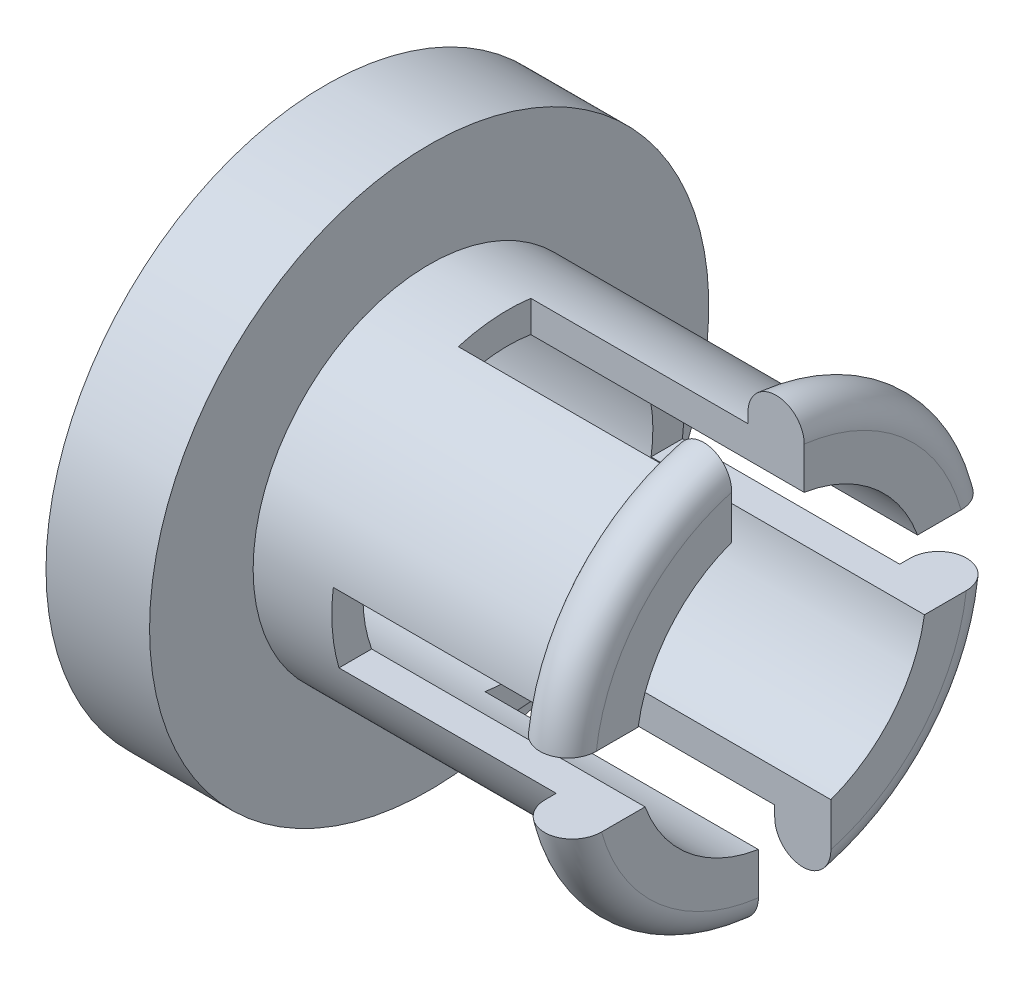
SolidWorks part; units mm, degrees
ref_plane "Front Plane" through (0, 0, 0) normal (0, 0, 1) x (1, 0, 0)
ref_plane "Top Plane" through (0, 0, 0) normal (0, 1, 0) x (1, 0, 0)
ref_plane "Right Plane" through (0, 0, 0) normal (1, 0, 0) x (0, 0, -1)
sketch "Sketch1" plane through (0, 0, 0) normal (0, 0, 1) x (1, 0, 0)
  line L1 (0, 0) -> (13.97, 0)
  line L3 (3.175, 5.3975) -> (12.2488, 5.3975)
  line L7 (0, 8.5725) -> (3.175, 8.5725)
  line L8 (3.175, 5.3975) -> (3.175, 8.5725)
  line L10 (12.2488, 5.715) -> (12.2488, 5.3975)
  line L11 (0, 8.5725) -> (0, 0)
  line L12 (13.97, 5.715) -> (13.97, 0)
  arc A0 (13.97, 5.715) -> (12.2488, 5.715) centre (13.1094, 5.715) ccw
  dimension "D4" = 0.8606
  dimension "D1" = 8.5725
  dimension "D2" = 3.175
  dimension "D3" = 3.175
  dimension "D5" = 0.3175
  dimension "D6" = 13.97
revolve "Revolve1" add sketch "Sketch1" angle 360 about L1
sketch "Sketch2" plane through (0, 0, 0) normal (-1, 0, 0) x (0, 0, 1)
  circle A0 centre (0, 0) radius 4.445
  dimension "D1" = 8.89
extrude "Cut-Extrude1" cut sketch "Sketch2" against normal blind 18.034
sketch "Sketch5" plane through (0, 0, 0) normal (0, 0, 1) x (1, 0, 0)
  line L0 (13.97, -5.715) -> (13.97, 5.715) construction
  line L1 (13.97, 1.5201) -> (5.588, 1.5201)
  line L2 (13.97, 1.5201) -> (13.97, -0.7024)
  line L3 (13.97, -0.7024) -> (5.588, -0.7024)
  line L4 (5.588, 1.5201) -> (5.588, -0.7024)
  line L5 (12.2488, 5.3975) -> (3.175, 5.3975) construction
  dimension "D1" = 2.2225
  dimension "D2" = 8.382
  dimension "D3" = 3.8774
extrude "Cut-Extrude2" cut sketch "Sketch5" against normal through all
pattern_circular "CirPattern1" count 4 over 360 about axis through (0, 0, 0) along (1, 0, 0) of "Cut-Extrude2"
